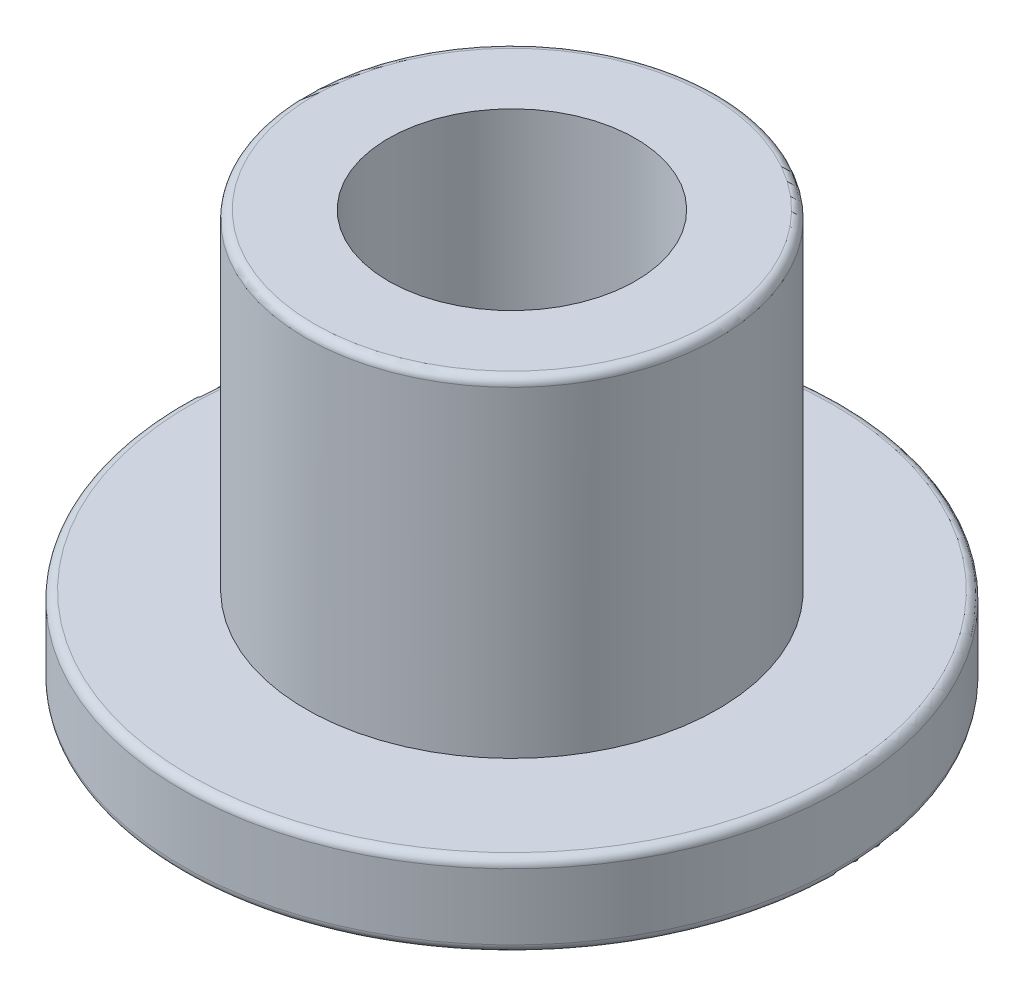
SolidWorks part; units mm, degrees
material "黄铜"
ref_plane "Front" through (0, 0, 0) normal (0, 0, 1) x (1, 0, 0)
ref_plane "Top" through (0, 0, 0) normal (0, 1, 0) x (1, 0, 0)
ref_plane "Right" through (0, 0, 0) normal (1, 0, 0) x (0, 0, -1)
sketch "草图1" plane through (0, 0, 0) normal (0, 1, 0) x (1, 0, 0)
  circle A0 centre (0, 0) radius 3
  circle A1 centre (0, 0) radius 5
  dimension "铜套内径" = 6
  dimension "铜套外径" = 10
extrude "凸台-拉伸1" add sketch "草图1" along normal mid plane 10
sketch "草图2" plane through (0, -5, 0) normal (0, -1, 0) x (1, 0, 0)
  circle A0 centre (0, 0) radius 8
  circle A1 centre (0, 0) radius 5
  circle A4 centre (0, 0) radius 5 construction
  dimension "翻边外径" = 16
extrude "凸台-拉伸2" add sketch "草图2" against normal blind 2 separate body
combine bodies "组合1" operation type add bodies to combine 102 101
fillet "圆角1" radius 0.2 3 edges at (0, -5, -8) (0, -3, -8) (0, 5, 5)
other "冻结***"
